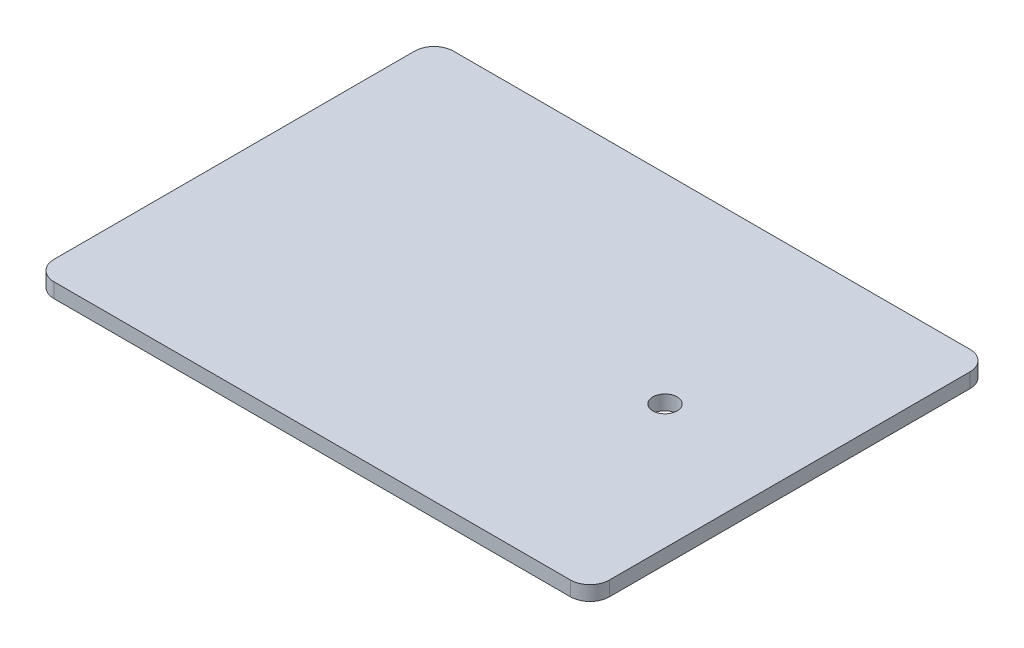
SolidWorks part; units mm, degrees
ref_plane "Front Plane" through (0, 0, 0) normal (0, 0, 1) x (1, 0, 0)
ref_plane "Top Plane" through (0, 0, 0) normal (0, 1, 0) x (1, 0, 0)
ref_plane "Right Plane" through (0, 0, 0) normal (1, 0, 0) x (0, 0, -1)
sketch "Sketch1" plane through (0, 0, 0) normal (0, 1, 0) x (1, 0, 0)
  line L1 (-53, 41) -> (53, 41)
  line L2 (-57, 37) -> (-57, -37)
  line L3 (-53, -41) -> (53, -41)
  line L4 (57, 37) -> (57, -37)
  line L5 (-57, 41) -> (57, -41) construction
  line L6 (-57, -41) -> (57, 41) construction
  arc A0 (-57, -37) -> (-53, -41) centre (-53, -37) ccw
  arc A1 (53, -41) -> (57, -37) centre (53, -37) ccw
  arc A2 (53, 41) -> (57, 37) centre (53, 37) cw
  arc A3 (-53, 41) -> (-57, 37) centre (-53, 37) ccw
  point P0 (0, 0)
  dimension "D3" = 4
  dimension "D1" = 114
  dimension "D2" = 82
extrude "Boss-Extrude1" add sketch "Sketch1" along normal blind 3
extrude "Cut-Extrude1" cut sketch "Sketch2" against normal blind 3
sketch "Sketch2" plane through (0, 0, 0) normal (0, -1, 0) x (1, 0, 0)
  circle A1 centre (31.4, 0) radius 2.5
